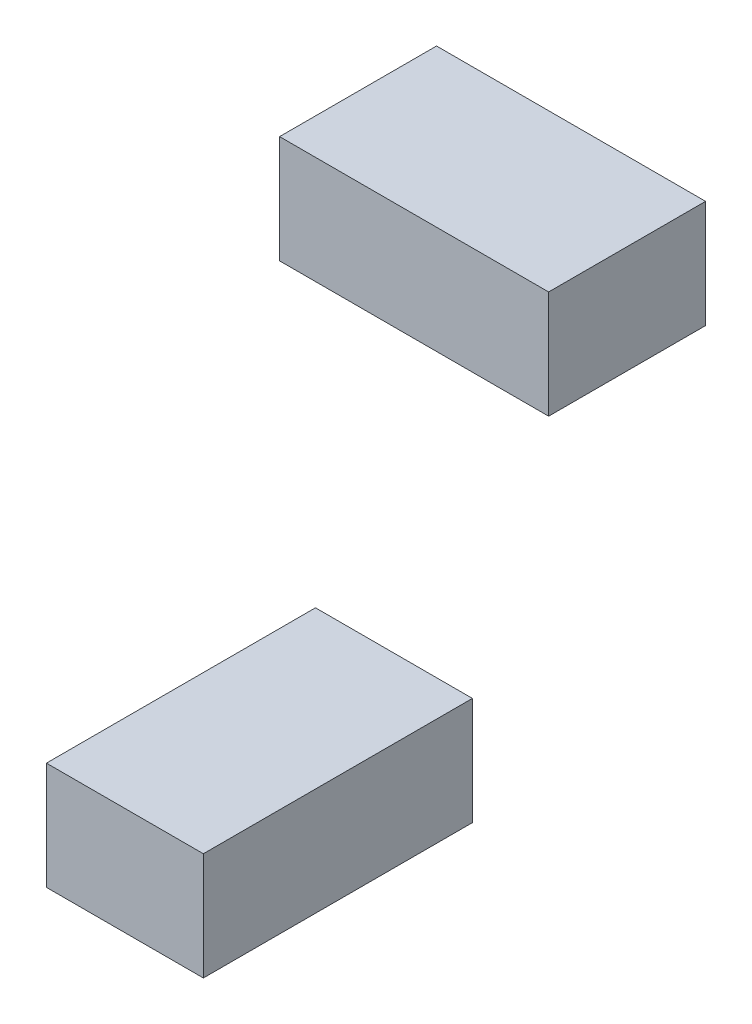
SolidWorks part; units mm, degrees
ref_plane "Front Plane" through (0, 0, 0) normal (0, 0, 1) x (1, 0, 0)
ref_plane "Top Plane" through (0, 0, 0) normal (0, 1, 0) x (1, 0, 0)
ref_plane "Right Plane" through (0, 0, 0) normal (1, 0, 0) x (0, 0, -1)
sketch "Sketch1" plane through (0, 0, 0) normal (0, 1, 0) x (1, 0, 0)
  line L0 (-10.16, -22.86) -> (-8.89, -25.4) construction
  line L1 (-10.16, 25.4) -> (10.16, 25.4) construction
  line L2 (-10.16, 25.4) -> (-10.16, -25.4) construction
  line L3 (-10.16, -25.4) -> (10.16, -25.4) construction
  line L4 (10.16, 25.4) -> (10.16, -25.4) construction
  line L5 (10.16, -22.86) -> (8.89, -25.4) construction
  line L7 (-3.937, 15.5448) -> (-4.826, 15.5448)
  line L8 (-3.937, 15.5448) -> (-3.937, 14.0208)
  line L9 (-3.937, 14.0208) -> (-4.826, 14.0208)
  line L10 (-4.826, 15.5448) -> (-4.826, 14.0208)
  line L11 (-5.715, 17.7546) -> (-7.239, 17.7546)
  line L12 (-5.715, 17.7546) -> (-5.715, 18.6436)
  line L13 (-5.715, 18.6436) -> (-7.239, 18.6436)
  line L14 (-7.239, 17.7546) -> (-7.239, 18.6436)
  point P4 (-10.16, 0)
  point P6 (0, 25.4)
  dimension "D1" = 20.32
  dimension "D2" = 50.8
  dimension "D3" = 1.27
  dimension "D4" = 2.54
  dimension "D5" = 0.889
  dimension "D6" = 1.524
  dimension "D7" = 6.223
  dimension "D8" = 11.3792
  dimension "D9" = 7.6454
  dimension "D10" = 4.445
extrude "Boss-Extrude1" add sketch "Sketch1" along normal blind 0.6096
